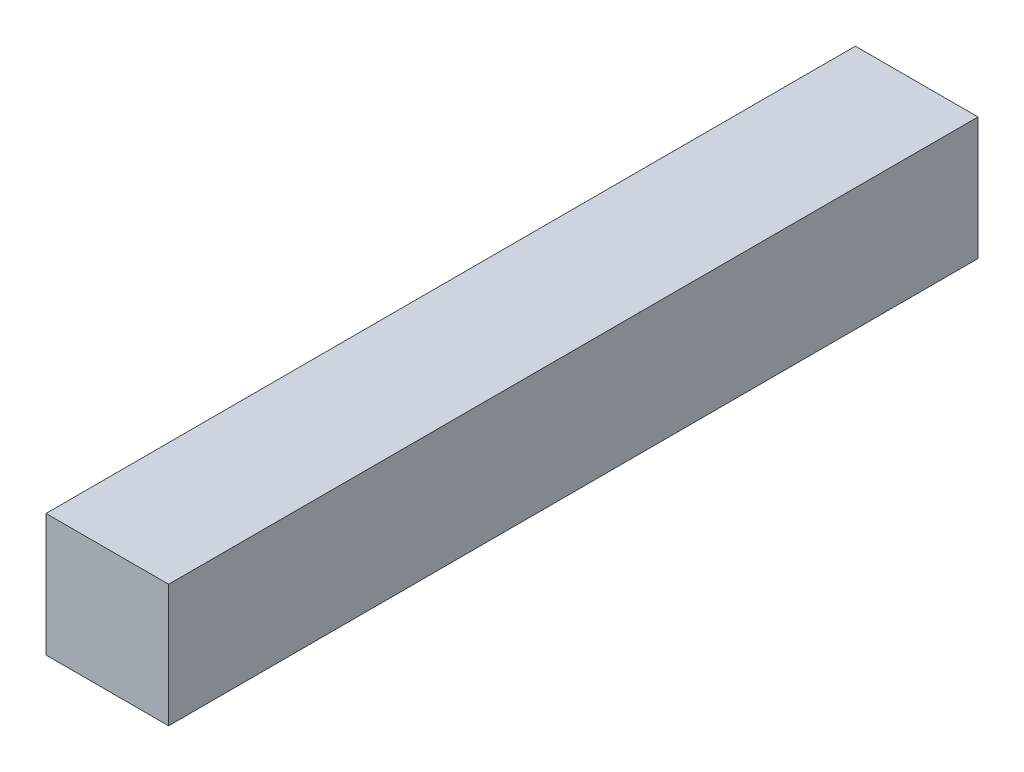
SolidWorks part; units mm, degrees
ref_plane "Спереди" through (0, 0, 0) normal (0, 0, 1) x (1, 0, 0)
ref_plane "Сверху" through (0, 0, 0) normal (0, 1, 0) x (1, 0, 0)
ref_plane "Справа" through (0, 0, 0) normal (1, 0, 0) x (0, 0, -1)
sketch "Эскиз1" plane through (0, 0, 0) normal (0, 0, 1) x (1, 0, 0)
  line L1 (-5, 5) -> (5, 5)
  line L2 (-5, 5) -> (-5, -5)
  line L3 (-5, -5) -> (5, -5)
  line L4 (5, 5) -> (5, -5)
  line L5 (-5, 5) -> (5, -5) construction
  line L6 (-5, -5) -> (5, 5) construction
  point P0 (0, 0)
extrude "Вытянуть1" add sketch "Эскиз1" along normal blind 66
